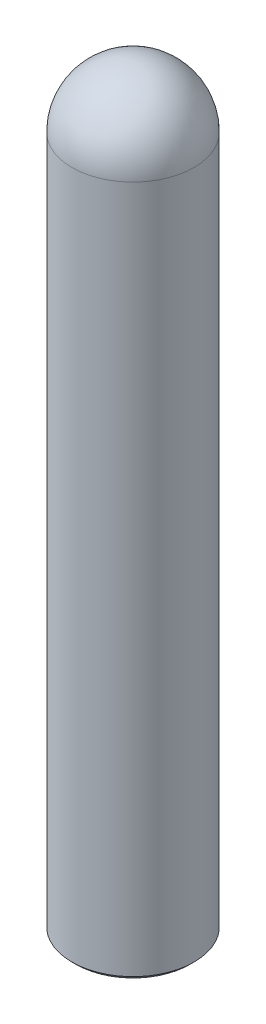
SolidWorks part; units mm, degrees
material "Custom Plastic"
ref_plane "Front Plane" through (0, 0, 0) normal (0, 0, 1) x (1, 0, 0)
ref_plane "Top Plane" through (0, 0, 0) normal (0, 1, 0) x (1, 0, 0)
ref_plane "Right Plane" through (0, 0, 0) normal (1, 0, 0) x (0, 0, -1)
sketch "Sketch1" plane through (0, 0, 0) normal (0, 1, 0) x (1, 0, 0)
  circle A0 centre (0, 0) radius 15
  dimension "D1" = 30
extrude "Boss-Extrude1" add sketch "Sketch1" along normal blind 185
fillet "Fillet1" radius 15 1 edges at (0, 185, 15)
sketch "Sketch2" plane through (0, 0, 0) normal (0, -1, 0) x (1, 0, 0)
  circle A0 centre (0, 0) radius 3.175
  dimension "D1" = 6.35
extrude "Cut-Extrude1" cut sketch "Sketch2" against normal blind 12
chamfer "Chamfer1" distance 0.4 angle 45 1 edges at (0, 0, -3.175)
chamfer "Chamfer2" distance 1 angle 45 1 edges at (0, 0, 15)
